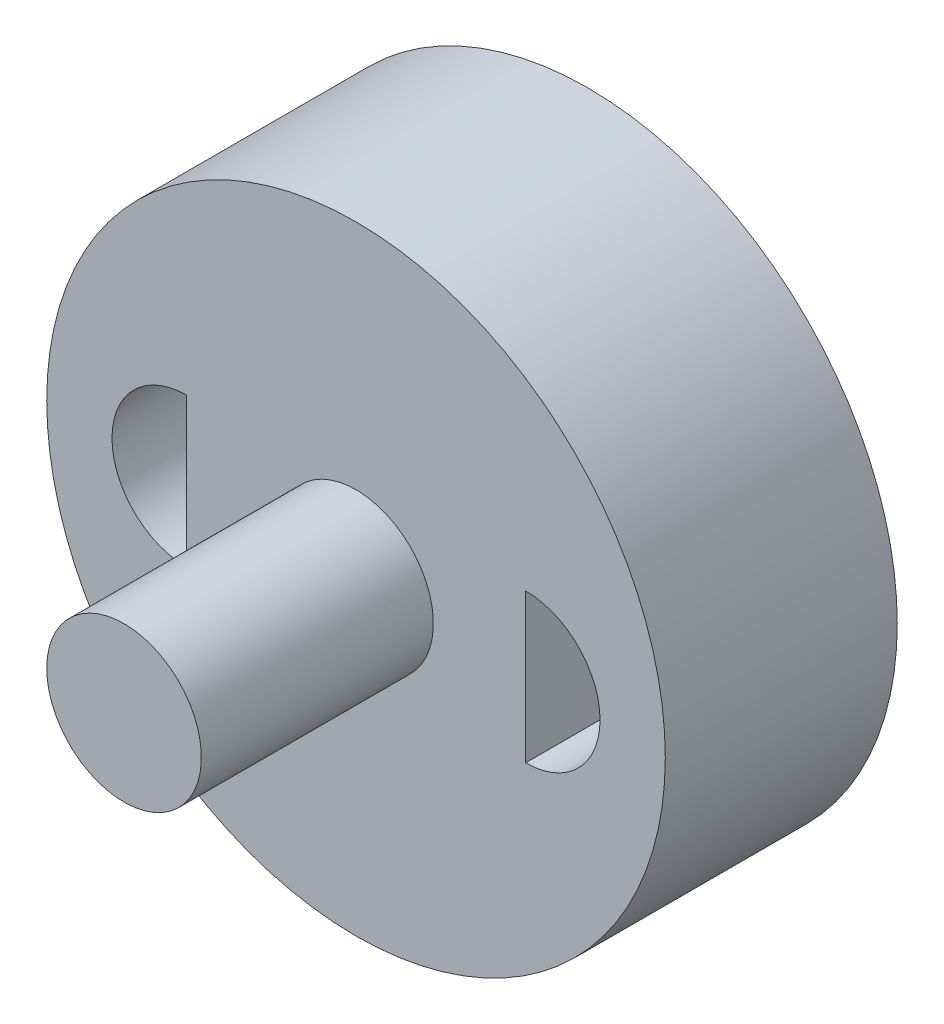
SolidWorks part; units mm, degrees
material "ABS"
ref_plane "Front Plane" through (0, 0, 0) normal (0, 0, 1) x (1, 0, 0)
ref_plane "Top Plane" through (0, 0, 0) normal (0, 1, 0) x (1, 0, 0)
ref_plane "Right Plane" through (0, 0, 0) normal (1, 0, 0) x (0, 0, -1)
sketch "Sketch1" plane through (0, 0, 0) normal (0, 0, 1) x (1, 0, 0)
  circle A0 centre (0, 0) radius 101.6
  point P23 (0, 0)
  dimension "D1" = 203.2
extrude "Boss-Extrude1" add sketch "Sketch1" along normal blind 76.2 contours A0
sketch "Sketch2" plane through (0, 0, 76.2) normal (0, 0, 1) x (1, 0, 0)
  line L8 (-55.703, 24.4622) -> (55.703, 24.4622)
  line L9 (-55.703, 24.4622) -> (-55.703, -24.4622)
  line L10 (-55.703, -24.4622) -> (55.703, -24.4622)
  line L11 (55.703, 24.4622) -> (55.703, -24.4622)
  line L12 (-55.703, 24.4622) -> (55.703, -24.4622) construction
  line L13 (-55.703, -24.4622) -> (55.703, 24.4622) construction
  arc A1 (55.703, -24.4622) -> (55.703, 24.4622) centre (55.703, 0) ccw
  arc A2 (-55.703, -24.4622) -> (-55.703, 24.4622) centre (-55.703, 0) cw
  point P0 (0, 0)
  point P14 (0, 0)
extrude "Cut-Extrude7" cut sketch "Sketch2" against normal through all both and the other way through all contours A2 L9 | L11 A1
sketch "Sketch3" plane through (0, 0, 76.2) normal (0, 0, 1) x (1, 0, 0)
  circle A0 centre (0, 0) radius 25.4
extrude "Boss-Extrude2" add sketch "Sketch3" along normal blind 76.2
